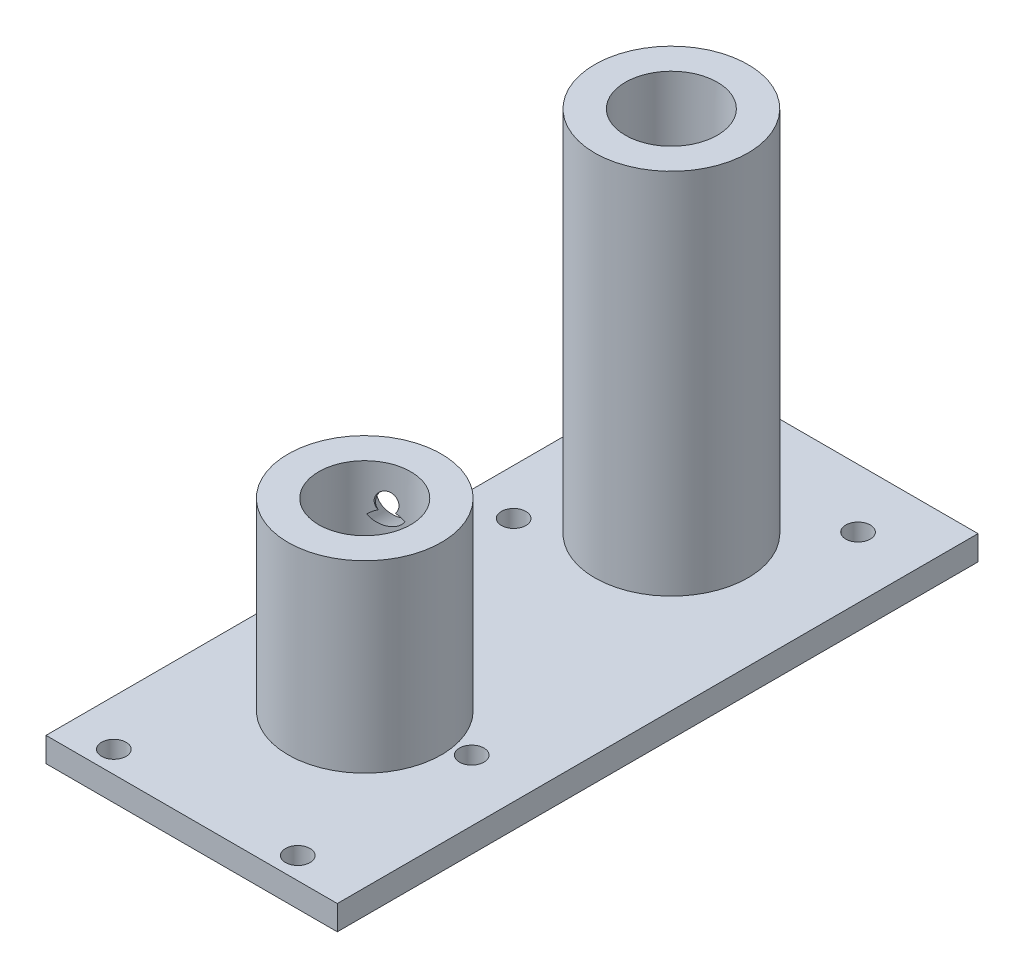
SolidWorks part; units mm, degrees
ref_plane "Płaszczyzna przednia" through (0, 0, 0) normal (0, 0, 1) x (1, 0, 0)
ref_plane "Płaszczyzna górna" through (0, 0, 0) normal (0, 1, 0) x (1, 0, 0)
ref_plane "Płaszczyzna prawa" through (0, 0, 0) normal (1, 0, 0) x (0, 0, -1)
sketch "Sketch1" plane through (0, 0, 0) normal (0, 1, 0) x (1, 0, 0)
  line L1 (-19.1477, 6.875) -> (-9.1477, 6.875)
  line L2 (-19.1477, 6.875) -> (-19.1477, -3.125)
  line L3 (-19.1477, -3.125) -> (-9.1477, -3.125)
  line L4 (-9.1477, 6.875) -> (-9.1477, -3.125)
  line L5 (-19.1477, 6.875) -> (-9.1477, -3.125) construction
  line L6 (-19.1477, -3.125) -> (-9.1477, 6.875) construction
  line L7 (-19.1477, -43.125) -> (-9.1477, -43.125)
  line L8 (-19.1477, -43.125) -> (-19.1477, -53.125)
  line L9 (-19.1477, -53.125) -> (-9.1477, -53.125)
  line L10 (-9.1477, -43.125) -> (-9.1477, -53.125)
  line L11 (-19.1477, -43.125) -> (-9.1477, -53.125) construction
  line L12 (-19.1477, -53.125) -> (-9.1477, -43.125) construction
  line L13 (-36.6477, 26.875) -> (10.8523, 26.875)
  line L14 (-36.6477, 26.875) -> (-36.6477, -83.125)
  line L15 (-36.6477, -83.125) -> (10.8523, -83.125)
  line L16 (10.8523, 26.875) -> (10.8523, -83.125)
  circle A0 centre (0.8523, 17.315) radius 2
  circle A1 centre (-29.1477, -8.845) radius 2
  circle A2 centre (0.8523, -45.685) radius 2
  circle A3 centre (0.8523, -74.045) radius 2
  circle A4 centre (-29.1477, -74.045) radius 2
  point P0 (-14.6023, 1.875)
  point P5 (-2.5568, 5.0568)
  dimension "D3" = 4
  dimension "D4" = 4
  dimension "D5" = 4
  dimension "D6" = 4
  dimension "D7" = 4
  dimension "D1" = 10
  dimension "D2" = 40
  dimension "D8" = 10
  dimension "D9" = 10.44
  dimension "D10" = 15.72
  dimension "D11" = 10
  dimension "D12" = 30.92
  dimension "D13" = 10
  dimension "D14" = 10
  dimension "D15" = 20.92
  dimension "D16" = 2.56
  dimension "D17" = 10
  dimension "D18" = 20
  dimension "D19" = 17.5
  dimension "D20" = 20
  dimension "D21" = 30
extrude "Boss-Extrude1" add sketch "Sketch1" against normal blind 4
sketch "Sketch2" plane through (0, 0, 0) normal (0, 1, 0) x (1, 0, 0)
  line L0 (-19.1477, -3.125) -> (-9.1477, 6.875) construction
  line L1 (-19.1477, -53.125) -> (-9.1477, -43.125) construction
  circle A2 centre (-14.1477, -48.125) radius 12.5
  circle A3 centre (-14.1477, -48.125) radius 7.5
  point P5 (-14.1477, 1.875)
  dimension "D3" = 2
extrude "Boss-Extrude2" add sketch "Sketch2" along normal blind 30 contours A2 | A3
sketch "Sketch4" plane through (0, 0, 0) normal (0, 1, 0) x (1, 0, 0)
  line L0 (-19.1477, 6.875) -> (-9.1477, -3.125) construction
  circle A0 centre (-14.1477, 1.875) radius 12.5
  circle A1 centre (-14.1477, 1.875) radius 7.5
  point P7 (-14.1477, 1.875)
  dimension "D1" = 15
  dimension "D2" = 25
extrude "Boss-Extrude3" add sketch "Sketch4" along normal blind 60
sketch "Szkic1" plane through (0, 0, 0) normal (0, 1, 0) x (1, 0, 0)
  line L0 (-36.6477, 26.875) -> (-36.6477, -83.125) construction
  line L1 (-36.6477, -77.6027) -> (10.8523, -77.6027)
  line L2 (-36.6477, -77.6027) -> (-36.6477, -83.125)
  line L3 (-36.6477, -83.125) -> (10.8523, -83.125)
  line L4 (10.8523, -77.6027) -> (10.8523, -83.125)
extrude "Wytnij-wyciągnięcie1" cut sketch "Szkic1" against normal blind 10.5
sketch "Szkic2" plane through (0, 60, 0) normal (0, 1, 0) x (1, 0, 0)
  line L0 (-14.1477, -48.125) -> (-44.1364, 16.186)
  line L1 (-14.1477, -48.125) -> (-14.1477, -14.0887) construction
  dimension "D1" = 25
ref_plane "Płaszczyzna1" through (-30.0538, 0, 14.0143) normal (0.9063, 0, -0.4226) x (-0.4226, 0, -0.9063)
sketch "Szkic3" plane through (-30.0538, 0, 14.0143) normal (0.9063, 0, -0.4226) x (-0.4226, 0, -0.9063)
  line L0 (-34.2607, 26.1292) -> (-15.2605, 17.9012) construction
  line L1 (-31.0383, 24.7337) -> (-30.434, 26.1292)
  line L2 (-30.434, 26.1292) -> (-29.168, 25.581)
  line L3 (-29.168, 25.581) -> (-28.5802, 26.9385)
  line L4 (-28.5802, 26.9385) -> (-22.1566, 24.1568)
  line L5 (-22.1566, 24.1568) -> (-23.3488, 21.4038)
  line L6 (-23.3488, 21.4038) -> (-31.0383, 24.7337)
  dimension "D1" = 3
  dimension "D2" = 7
revolve "Wycięcie-obrót1" cut sketch "Szkic3" angle 360 about L0
pattern_linear "Szyk liniowy1" count 2 spacing 50 along (0, 0, -1) of "Wycięcie-obrót1"
